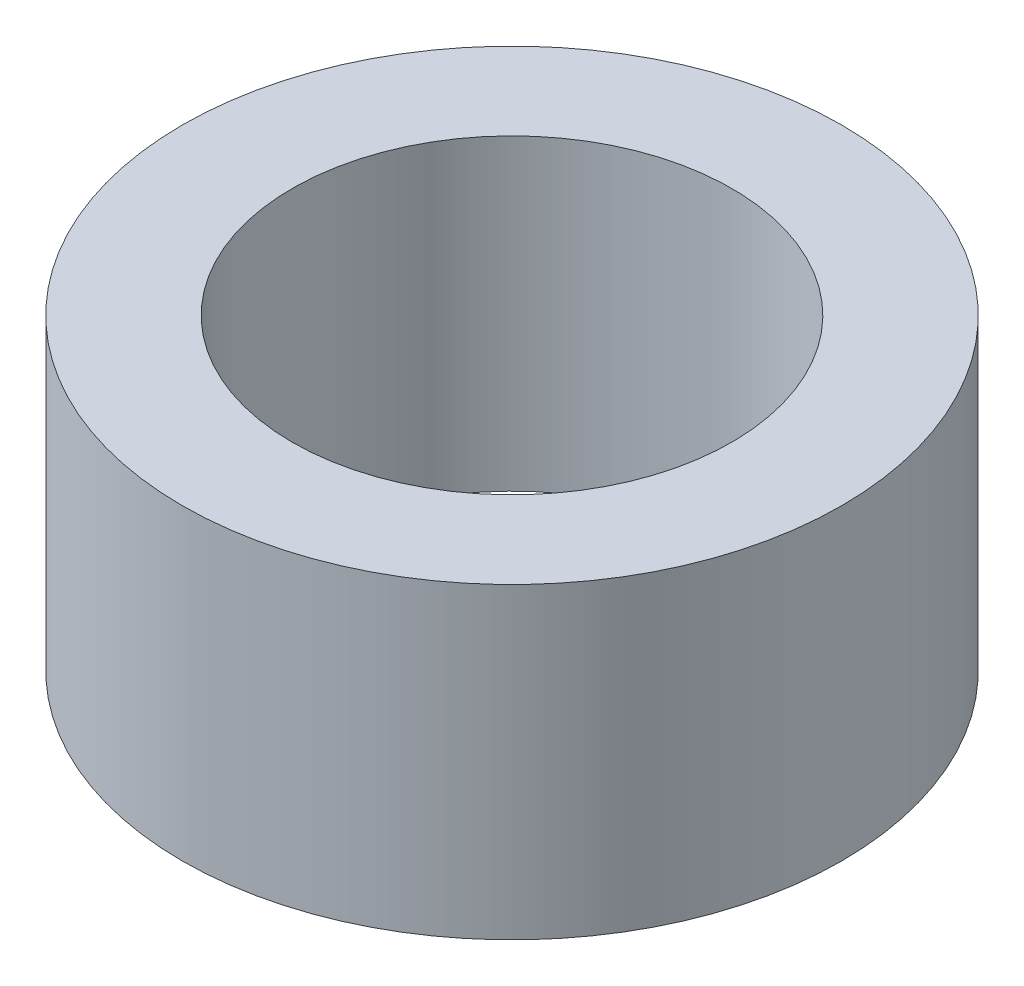
SolidWorks part; units mm, degrees
ref_plane "Front Plane" through (0, 0, 0) normal (0, 0, 1) x (1, 0, 0)
ref_plane "Top Plane" through (0, 0, 0) normal (0, 1, 0) x (1, 0, 0)
ref_plane "Right Plane" through (0, 0, 0) normal (1, 0, 0) x (0, 0, -1)
sketch "Sketch1" plane through (0, 0, 0) normal (0, 1, 0) x (1, 0, 0)
  circle A0 centre (0, 0) radius 20
  circle A1 centre (0, 0) radius 30
  dimension "D1" = 60
  dimension "D2" = 40
extrude "Boss-Extrude1" add sketch "Sketch1" along normal mid plane 28
